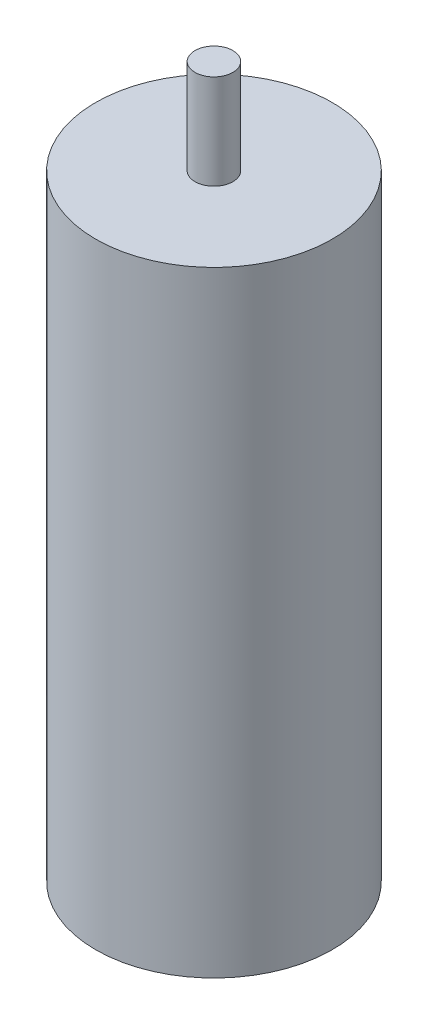
SolidWorks part; units mm, degrees
ref_plane "Alzado" through (0, 0, 0) normal (1, 0, 0) x (0, 1, 0)
ref_plane "Planta" through (0, 0, 0) normal (0, 0, 1) x (0, 1, 0)
ref_plane "Vista lateral" through (0, 0, 0) normal (0, 1, 0) x (-1, 0, 0)
sketch "Croquis1" plane through (0, 0, 0) normal (0, 1, 0) x (-1, 0, 0)
  circle A0 centre (0, 0) radius 12.5
  dimension "D1" = 25
extrude "Saliente-Extruir1" add sketch "Croquis1" along normal blind 65
sketch "Croquis2" plane through (0, 65, 0) normal (0, 1, 0) x (-1, 0, 0)
  circle A0 centre (0, 0) radius 2
  dimension "D1" = 4
extrude "Saliente-Extruir2" add sketch "Croquis2" along normal blind 10
